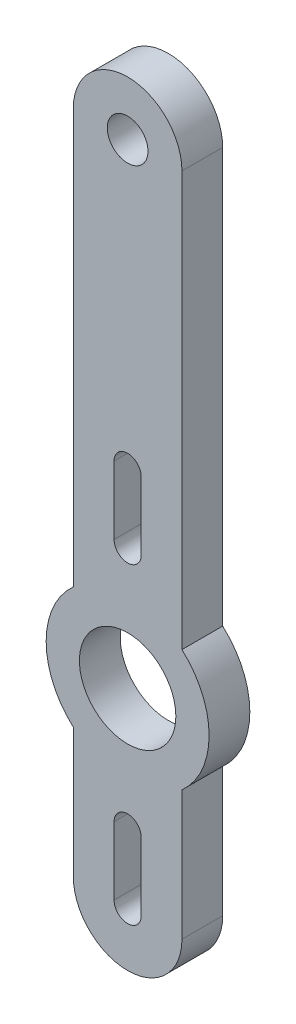
SolidWorks part; units mm, degrees
material "Balsa"
ref_plane "Front Plane" through (0, 0, 0) normal (0, 0, 1) x (1, 0, 0)
ref_plane "Top Plane" through (0, 0, 0) normal (0, 1, 0) x (1, 0, 0)
ref_plane "Right Plane" through (0, 0, 0) normal (1, 0, 0) x (0, 0, -1)
sketch "Sketch1" plane through (0, 0, 0) normal (0, 0, 1) x (1, 0, 0)
  line L0 (0, -4) -> (0, 53) construction
  line L1 (4, 0) -> (4, 9.5279)
  line L2 (-4, 0) -> (-4, 9.5279)
  line L3 (0, 0) -> (0, 5) construction
  line L4 (-1, 0) -> (-1, 5)
  line L5 (1, 0) -> (1, 5)
  line L6 (4, 18.4721) -> (4, 49)
  line L7 (-4, 18.4721) -> (-4, 49)
  line L8 (-10.0773, 14) -> (15.9989, 14) construction
  line L9 (0, 28) -> (0, 23) construction
  line L10 (-1, 28) -> (-1, 23)
  line L11 (1, 28) -> (1, 23)
  arc A0 (-4, 0) -> (4, 0) centre (0, 0) ccw
  arc A1 (-1, 0) -> (1, 0) centre (0, 0) ccw
  arc A2 (1, 5) -> (-1, 5) centre (0, 5) ccw
  circle A3 centre (0, 14) radius 3.55
  arc A4 (4, 9.5279) -> (4, 18.4721) centre (0, 14) ccw
  arc A5 (4, 49) -> (-4, 49) centre (0, 49) ccw
  circle A6 centre (0, 49) radius 1.5
  arc A7 (-4, 18.4721) -> (-4, 9.5279) centre (0, 14) ccw
  arc A8 (-1, 28) -> (1, 28) centre (0, 28) cw
  arc A9 (1, 23) -> (-1, 23) centre (0, 23) cw
  point P4 (0, 2.5)
  point P23 (0, 53)
  point P27 (0, 25.5)
  dimension "D2" = 8
  dimension "D3" = 1
  dimension "D6" = 7.1
  dimension "D7" = 12
  dimension "D8" = 3
  dimension "D1" = 57
  dimension "D4" = 5
  dimension "D5" = 35
extrude "Boss-Extrude1" add sketch "Sketch1" along normal blind 3
